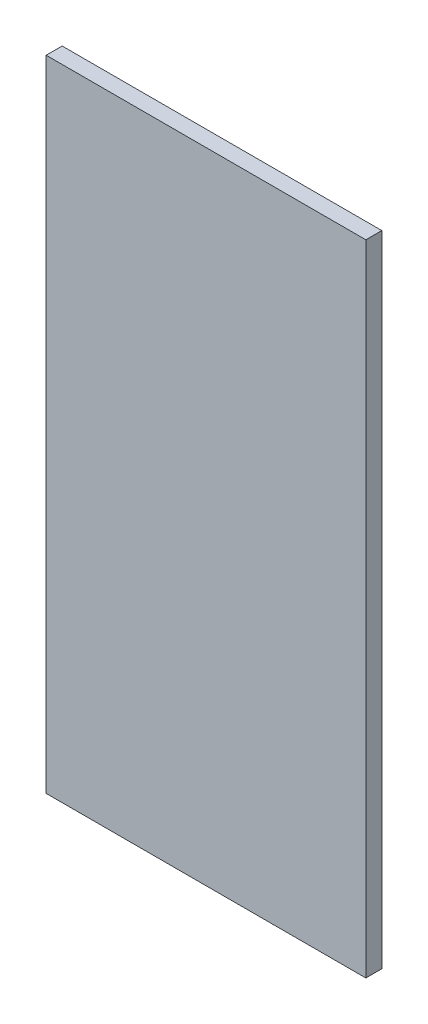
SolidWorks part; units mm, degrees
ref_plane "Front" through (0, 0, 0) normal (0, 0, 1) x (1, 0, 0)
ref_plane "Top" through (0, 0, 0) normal (0, 1, 0) x (1, 0, 0)
ref_plane "Right" through (0, 0, 0) normal (1, 0, 0) x (0, 0, -1)
sketch "Esquisse1" plane through (0, 0, 0) normal (0, 0, 1) x (1, 0, 0)
  line L1 (0, 0) -> (600, 0)
  line L2 (0, 0) -> (0, 1200)
  line L3 (0, 1200) -> (600, 1200)
  line L4 (600, 0) -> (600, 1200)
  dimension "D1" = 600
  dimension "D2" = 1200
extrude "Boss.-Extru.1" add sketch "Esquisse1" along normal blind 30
